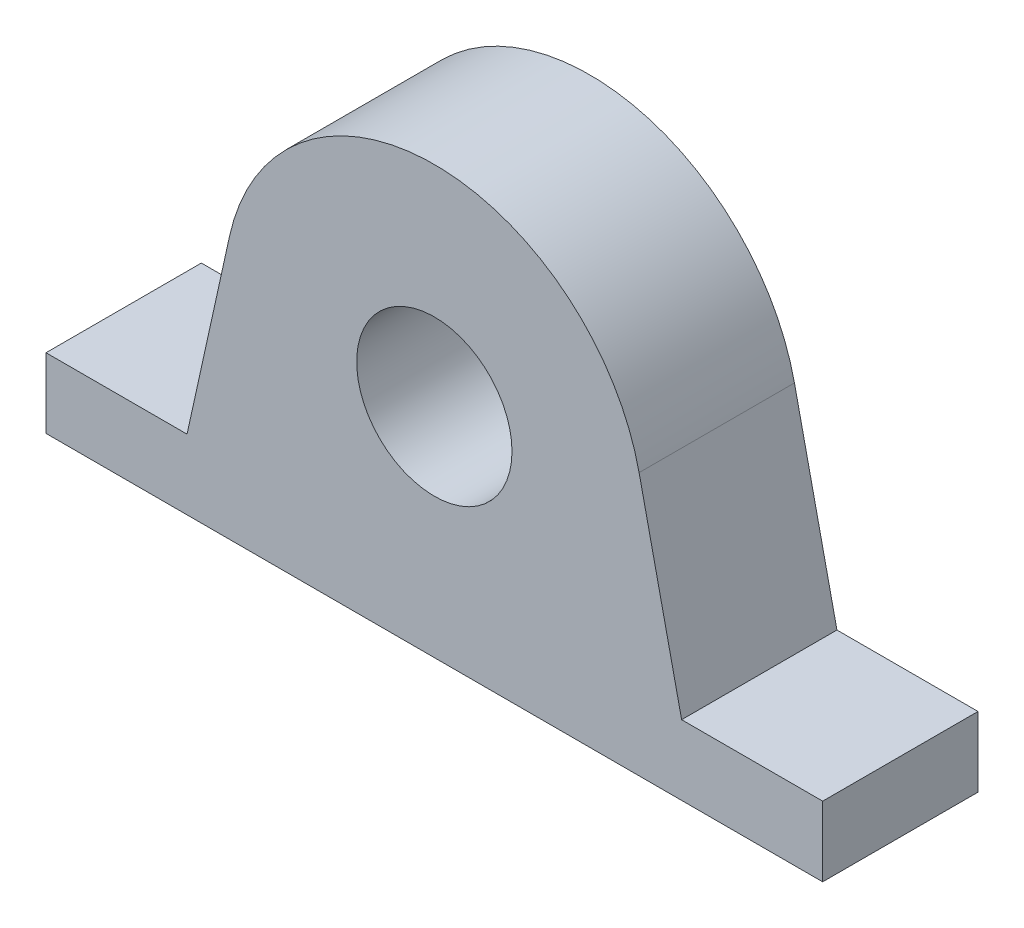
SolidWorks part; units mm, degrees
ref_plane "Front" through (0, 0, 0) normal (0, 0, 1) x (1, 0, 0)
ref_plane "Top" through (0, 0, 0) normal (0, 1, 0) x (1, 0, 0)
ref_plane "Right" through (0, 0, 0) normal (1, 0, 0) x (0, 0, -1)
sketch "Skizze1" plane through (0, 0, 0) normal (0, 0, 1) x (1, 0, 0)
  line L0 (0, 0) -> (0, 28.2636) construction
  line L1 (50, 0) -> (-50, 0)
  line L2 (-50, 0) -> (-50, 9)
  line L3 (-50, 9) -> (-31.8398, 9)
  line L4 (-31.8398, 9) -> (-26.3662, 33.8156)
  line L5 (31.8398, 9) -> (26.3662, 33.8156)
  line L6 (50, 9) -> (31.8398, 9)
  line L7 (50, 0) -> (50, 9)
  arc A0 (-26.3662, 33.8156) -> (26.3662, 33.8156) centre (0, 28) cw
  circle A1 centre (0, 28) radius 10
  dimension "D4" = 20
  dimension "D1" = 100
  dimension "D2" = 9
  dimension "D3" = 28
extrude "Aufsatz-Linear austragen1" add sketch "Skizze1" along normal blind 20
